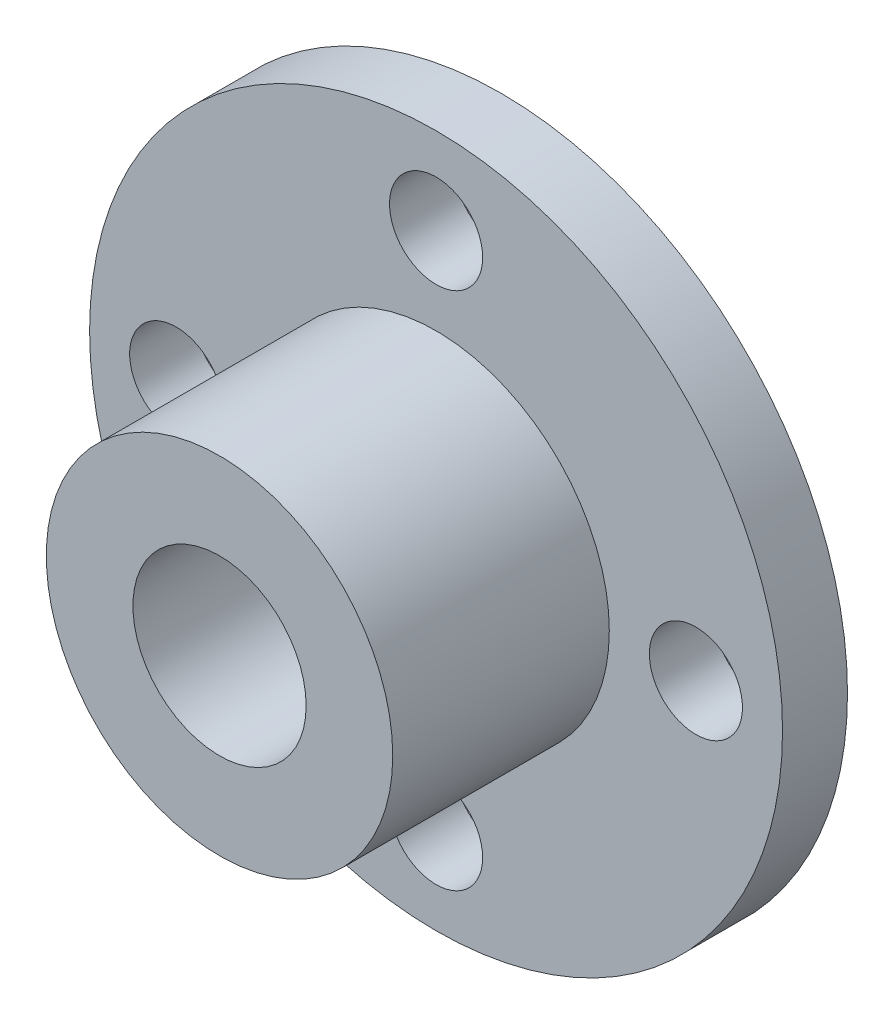
SolidWorks part; units mm, degrees
ref_plane "前视基准面" through (0, 0, 0) normal (0, 0, 1) x (1, 0, 0)
ref_plane "上视基准面" through (0, 0, 0) normal (0, 1, 0) x (1, 0, 0)
ref_plane "右视基准面" through (0, 0, 0) normal (1, 0, 0) x (0, 0, -1)
sketch "草图1" plane through (0, 0, 0) normal (0, 0, 1) x (1, 0, 0)
  circle A0 centre (0, 0) radius 16
  circle A1 centre (0, 12) radius 2.15
  circle A2 centre (0, -12) radius 2.15
  circle A3 centre (-12, 0) radius 2.15
  circle A4 centre (12, 0) radius 2.15
  circle A5 centre (0, 0) radius 8
  circle A6 centre (0, 0) radius 4
extrude "凸台-拉伸2" add sketch "草图1" along normal blind 3 contours A0 A5 A4 A3 A2 A1 | A5 A6 | A6
sketch "草图2" plane through (0, 0, 3) normal (0, 0, 1) x (1, 0, 0)
  circle A0 centre (0, 0) radius 4
  circle A1 centre (0, 0) radius 8
extrude "凸台-拉伸3" add sketch "草图2" along normal blind 10
